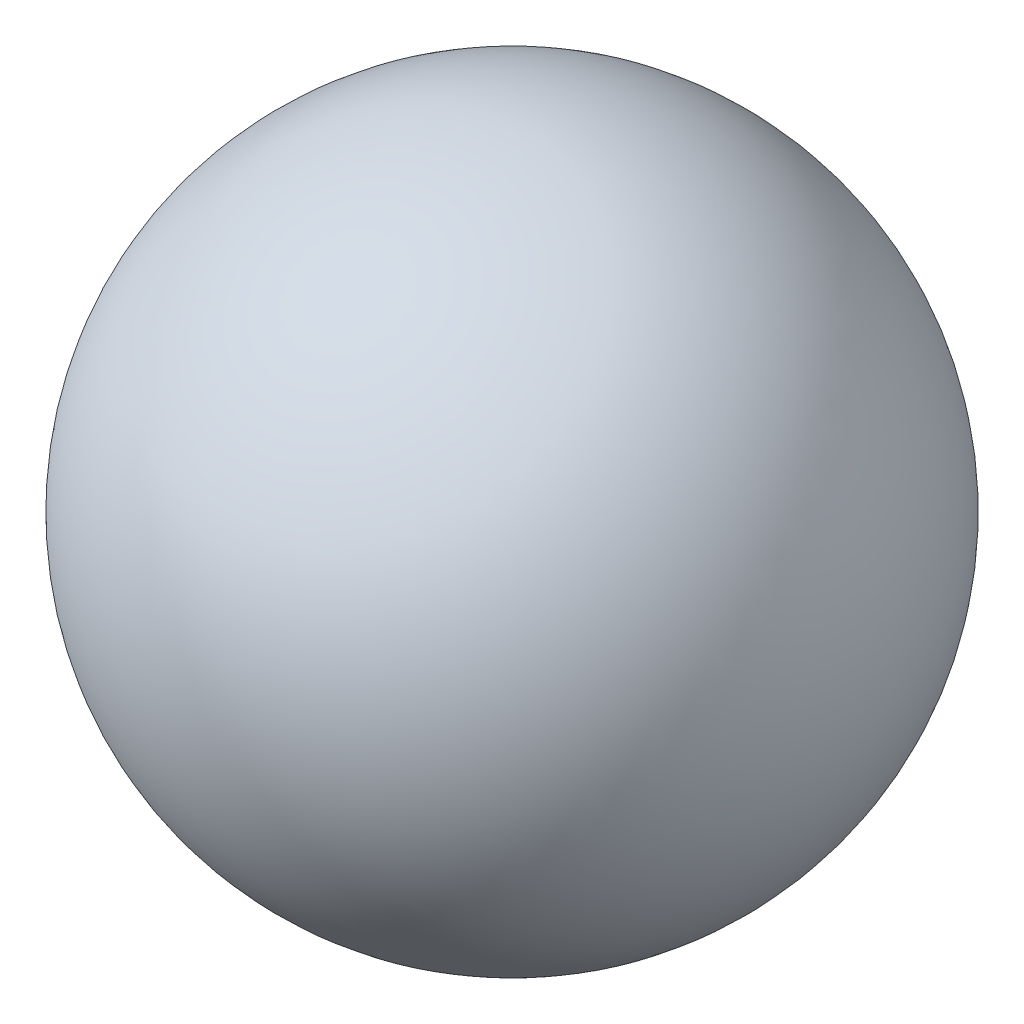
SolidWorks part; units mm, degrees
ref_plane "Front" through (0, 0, 0) normal (0, 0, 1) x (1, 0, 0)
ref_plane "Top" through (0, 0, 0) normal (0, 1, 0) x (1, 0, 0)
ref_plane "Right" through (0, 0, 0) normal (1, 0, 0) x (0, 0, -1)
sketch "Sketch2" plane through (0, 0, 0) normal (0, 0, 1) x (1, 0, 0)
  line L0 (0, 50.8) -> (0, -50.8) construction
  line L1 (0, 50.8) -> (0, -50.8)
  arc A0 (0, 50.8) -> (0, -50.8) centre (0, 0) ccw
  dimension "D1" = 101.6
revolve "Revolve1" add sketch "Sketch2" angle 360 about L0
